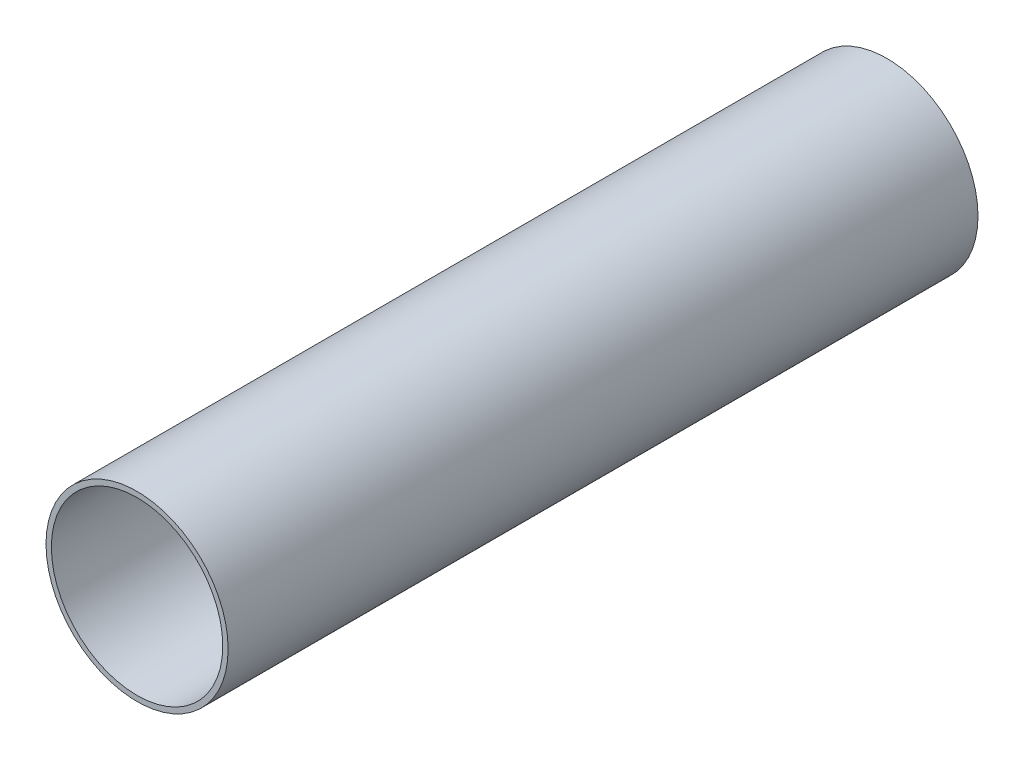
SolidWorks part; units mm, degrees
ref_plane "Front Plane" through (0, 0, 0) normal (0, 0, 1) x (1, 0, 0)
ref_plane "Top Plane" through (0, 0, 0) normal (0, 1, 0) x (1, 0, 0)
ref_plane "Right Plane" through (0, 0, 0) normal (1, 0, 0) x (0, 0, -1)
sketch "Sketch1" plane through (0, 0, 0) normal (0, 0, 1) x (1, 0, 0)
  circle A0 centre (0, 0) radius 25.5
  circle A1 centre (0, 0) radius 24
  dimension "D1" = 51
  dimension "D2" = 48
extrude "Boss-Extrude1" add sketch "Sketch1" along normal blind 210
sketch "Sketch2" plane through (0, 0, 0) normal (0, 0, -1) x (-1, 0, 0)
  circle A0 centre (0, 0) radius 29.3764
